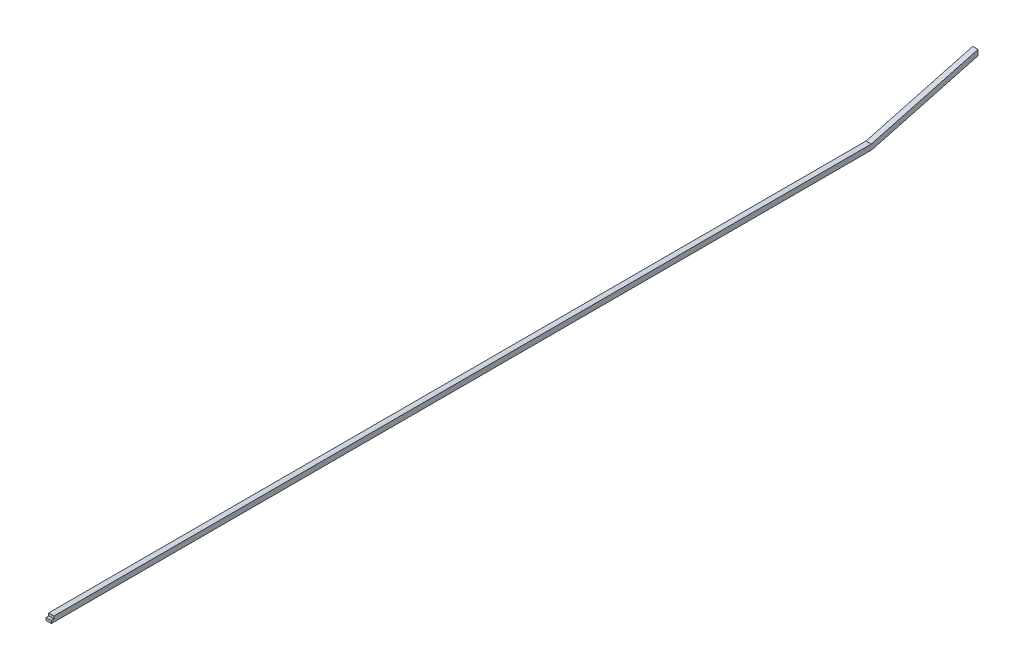
SolidWorks part; units mm, degrees
ref_plane "Спереди" through (0, 0, 0) normal (0, 0, 1) x (1, 0, 0)
ref_plane "Сверху" through (0, 0, 0) normal (0, 1, 0) x (1, 0, 0)
ref_plane "Справа" through (0, 0, 0) normal (1, 0, 0) x (0, 0, -1)
other "Configuration Table"
sketch "Эскиз1" plane through (0, 0, 0) normal (1, 0, 0) x (0, 0, -1)
  line L0 (-413.957, 0) -> (514.903, 0)
  line L1 (514.903, 0) -> (634.9, 32.1531)
  line L2 (-410.957, 6) -> (514.1131, 6)
  line L3 (-413.957, 0) -> (-413.957, 3)
  line L4 (-413.957, 3) -> (-410.957, 3)
  line L5 (-410.957, 3) -> (-410.957, 6)
  line L6 (514.903, 0) -> (513.9872, 6.9562) construction
  line L7 (634.9, 32.1531) -> (634.9, 38.3647)
  line L8 (514.1131, 6) -> (634.9, 38.3647)
  dimension "D1" = 928.86
  dimension "D2" = 15
  dimension "D3" = 124.23
  dimension "D4" = 3
  dimension "D5" = 3
  dimension "D6" = 3
  dimension "D7" = 82.5
  dimension "D8" = 7.0163
extrude "Бобышка-Вытянуть1" add sketch "Эскиз1" along normal blind 6
